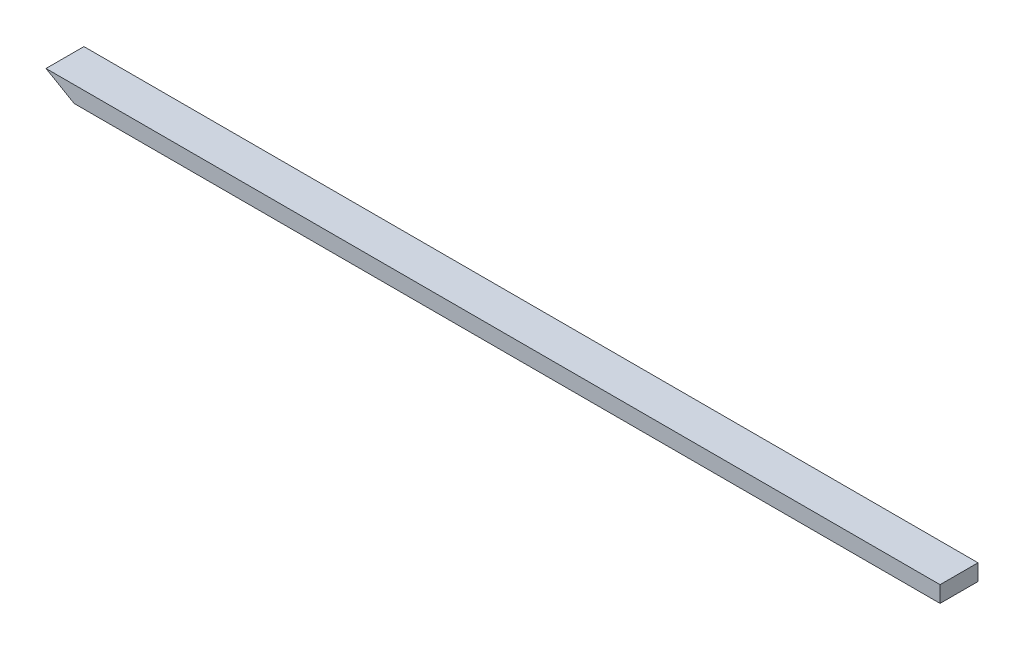
SolidWorks part; units mm, degrees
material "Pine"
ref_plane "Front Plane" through (0, 0, 0) normal (0, 0, 1) x (1, 0, 0)
ref_plane "Top Plane" through (0, 0, 0) normal (0, 1, 0) x (1, 0, 0)
ref_plane "Right Plane" through (0, 0, 0) normal (1, 0, 0) x (0, 0, -1)
sketch "Sketch1" plane through (0, 0, 0) normal (1, 0, 0) x (0, 0, -1)
  line L1 (-44.45, -19.05) -> (44.45, -19.05)
  line L2 (-44.45, -19.05) -> (-44.45, 19.05)
  line L3 (-44.45, 19.05) -> (44.45, 19.05)
  line L4 (44.45, -19.05) -> (44.45, 19.05)
  line L5 (-44.45, -19.05) -> (44.45, 19.05) construction
  line L6 (-44.45, 19.05) -> (44.45, -19.05) construction
  point P0 (0, 0)
  dimension "D1" = 38.1
  dimension "D2" = 88.9
extrude "Boss-Extrude1" add sketch "Sketch1" along normal mid plane 2095.5
sketch "Sketch3" plane through (0, 0, 0) normal (0, 0, 1) x (1, 0, 0)
  line L0 (-1047.75, 19.05) -> (-981.7589, -19.05)
  line L1 (1047.75, -19.05) -> (-1047.75, -19.05) construction
  line L2 (-981.7589, -19.05) -> (-1047.75, -19.05)
  line L3 (-1047.75, -19.05) -> (-1047.75, 19.05)
  line L4 (1047.75, 19.05) -> (-1047.75, 19.05) construction
  dimension "D1" = 30
extrude "Cut-Extrude1" cut sketch "Sketch3" against normal through all both and the other way through all contours L0 L2 L3
